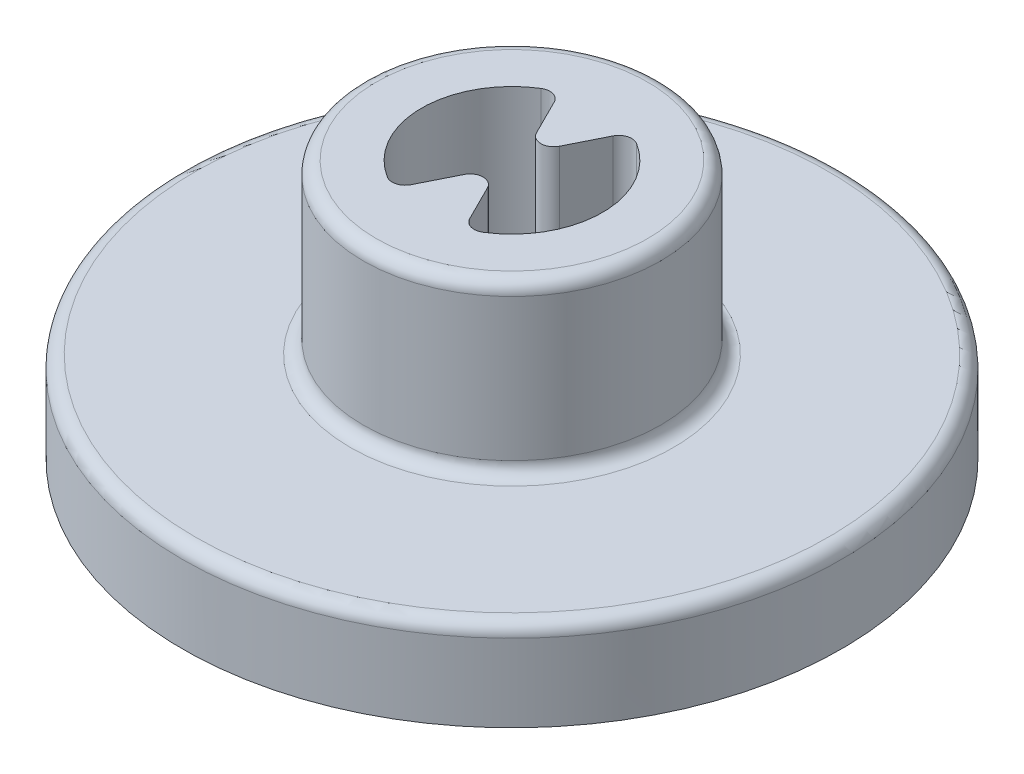
SolidWorks part; units mm, degrees
ref_plane "Front Plane" through (0, 0, 0) normal (0, 0, 1) x (1, 0, 0)
ref_plane "Top Plane" through (0, 0, 0) normal (0, 1, 0) x (1, 0, 0)
ref_plane "Right Plane" through (0, 0, 0) normal (1, 0, 0) x (0, 0, -1)
sketch "Sketch1" plane through (0, 0, 0) normal (0, 1, 0) x (1, 0, 0)
  circle A0 centre (0, 0) radius 12.75
  dimension "D1" = 25.5
extrude "Boss-Extrude2" add sketch "Sketch1" along normal blind 3.5
sketch "Sketch2" plane through (0, 3.5, 0) normal (0, 1, 0) x (1, 0, 0)
  circle A0 centre (0, 0) radius 5.75
  dimension "D1" = 11.5
extrude "Boss-Extrude3" add sketch "Sketch2" along normal blind 6.5
sketch "Sketch3" plane through (0, 10, 0) normal (0, 1, 0) x (1, 0, 0)
  line L2 (-0.4472, 1.3944) -> (-1.1359, 2.7719)
  line L3 (0.4472, 1.3944) -> (1.1359, 2.7719)
  line L4 (0, 0) -> (-5.75, 0) construction
  line L5 (-0.4472, -1.3944) -> (-1.1359, -2.7719)
  line L6 (0.4472, -1.3944) -> (1.1359, -2.7719)
  arc A0 (-1.847, 2.973) -> (-1.847, -2.973) centre (0, 0) ccw
  circle A1 centre (0, 0) radius 5.75 construction
  circle A2 centre (0, 0) radius 5.75 construction
  arc A3 (1.847, -2.973) -> (1.847, 2.973) centre (0, 0) ccw
  arc A4 (0.4472, 1.3944) -> (-0.4472, 1.3944) centre (0, 1.618) cw
  arc A5 (0.4472, -1.3944) -> (-0.4472, -1.3944) centre (0, -1.618) ccw
  arc A6 (-1.1359, -2.7719) -> (-1.847, -2.973) centre (-1.5831, -2.5483) cw
  arc A7 (1.847, -2.973) -> (1.1359, -2.7719) centre (1.5831, -2.5483) cw
  arc A8 (1.847, 2.973) -> (1.1359, 2.7719) centre (1.5831, 2.5483) ccw
  arc A9 (-1.1359, 2.7719) -> (-1.847, 2.973) centre (-1.5831, 2.5483) ccw
  point P6 (0, 3.5)
  point P15 (0, 0.5)
  point P19 (0, -0.5)
  dimension "D1" = 7
  dimension "D2" = 0.5
  dimension "D3" = 0.5
  dimension "D4" = 0.5
  dimension "D5" = 0.5
  dimension "D6" = 0.5
  dimension "D7" = 0.5
extrude "Cut-Extrude1" cut sketch "Sketch3" against normal blind 10
fillet "Fillet3" radius 0.5 2 edges at (0, 3.5, 12.75) (0, 3.5, 5.75)
fillet "Fillet4" radius 0.5 1 edges at (0, 10, 5.75)
